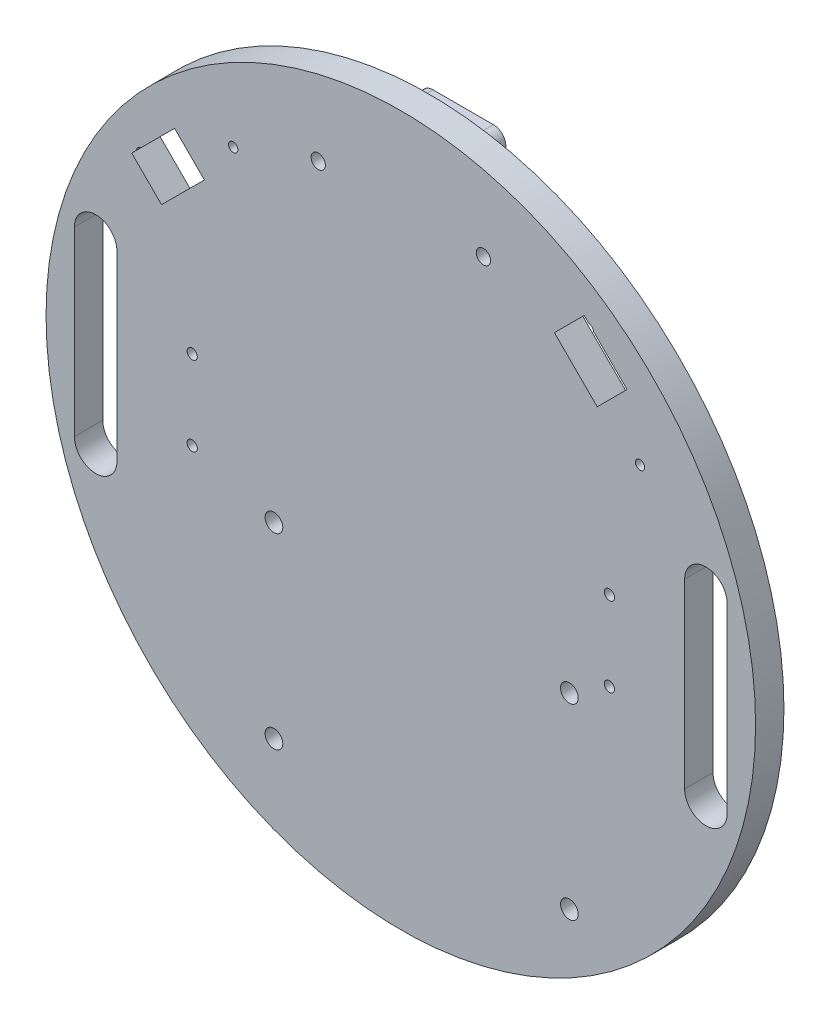
SolidWorks part; units mm, degrees
ref_plane "Front Plane" through (0, 0, 0) normal (0, 0, 1) x (1, 0, 0)
ref_plane "Top Plane" through (0, 0, 0) normal (0, 1, 0) x (1, 0, 0)
ref_plane "Right Plane" through (0, 0, 0) normal (1, 0, 0) x (0, 0, -1)
sketch "Master" plane through (0, 0, 0) normal (0, 0, 1) x (1, 0, 0)
  line L0 (-46.6725, -8.89) -> (-46.6725, 8.89) construction
  line L1 (-53.5313, 34.3674) -> (-34.3674, 53.5313) construction
  line L2 (-79.375, -79.375) -> (79.375, -79.375) construction
  line L3 (-79.375, -79.375) -> (-79.375, 79.375) construction
  line L4 (-79.375, 79.375) -> (79.375, 79.375) construction
  line L5 (79.375, -79.375) -> (79.375, 79.375) construction
  line L6 (-79.375, -79.375) -> (79.375, 79.375) construction
  line L7 (-68.2625, 20.32) -> (-68.2625, -20.32) construction
  line L8 (-63.5, 20.32) -> (-63.5, -20.32)
  line L9 (-73.025, 20.32) -> (-73.025, -20.32)
  line L10 (0, 79.375) -> (0, -79.375) construction
  line L11 (68.2625, 20.32) -> (68.2625, -20.32) construction
  line L14 (-18.4785, 60.3123) -> (18.4785, 60.3123) construction
  line L15 (-28.39, -14.615) -> (37.71, -14.615) construction
  line L16 (-28.39, -14.615) -> (-28.39, -56.515) construction
  line L17 (-28.39, -56.515) -> (37.71, -56.515) construction
  line L18 (37.71, -14.615) -> (37.71, -56.515) construction
  line L19 (-14.732, 66.8782) -> (14.732, 66.8782) construction
  line L20 (-14.732, 66.8782) -> (-14.732, 64.0588) construction
  line L21 (-43, -8.255) -> (43, -8.255) construction
  line L22 (-43, -8.255) -> (-43, -62.865) construction
  line L23 (-43, -62.865) -> (43, -62.865) construction
  line L24 (43, -8.255) -> (43, -62.865) construction
  line L25 (-43, -8.255) -> (43, -62.865) construction
  line L26 (-43, -62.865) -> (43, -8.255) construction
  line L27 (-14.732, 53.7718) -> (14.732, 53.7718) construction
  line L28 (14.732, 66.8782) -> (14.732, 64.0588) construction
  line L29 (-14.732, 66.8782) -> (14.732, 53.7718) construction
  line L30 (-14.732, 53.7718) -> (14.732, 66.8782) construction
  line L31 (-18.4785, 64.0588) -> (-14.732, 64.0588) construction
  line L32 (-18.4785, 56.5658) -> (-14.732, 56.5658) construction
  line L33 (14.732, 64.0588) -> (18.4785, 64.0588) construction
  line L34 (14.732, 56.5658) -> (18.4785, 56.5658) construction
  line L35 (-14.732, 56.5658) -> (-14.732, 53.7718) construction
  line L36 (14.732, 56.5658) -> (14.732, 53.7718) construction
  line L37 (-79.375, 79.375) -> (79.375, -79.375) construction
  line L38 (-53.5313, 34.3674) -> (-61.2184, 42.0545) construction
  line L39 (-61.2184, 42.0545) -> (-42.0545, 61.2184) construction
  line L40 (-34.3674, 53.5313) -> (-42.0545, 61.2184) construction
  line L41 (-53.5313, 34.3674) -> (-42.0545, 61.2184) construction
  line L42 (-61.2184, 42.0545) -> (-34.3674, 53.5313) construction
  line L43 (34.3674, 53.5313) -> (53.5313, 34.3674) construction
  line L44 (34.3674, 53.5313) -> (42.0545, 61.2184) construction
  line L45 (42.0545, 61.2184) -> (61.2184, 42.0545) construction
  line L46 (53.5313, 34.3674) -> (61.2184, 42.0545) construction
  line L47 (34.3674, 53.5313) -> (61.2184, 42.0545) construction
  line L48 (42.0545, 61.2184) -> (53.5313, 34.3674) construction
  line L49 (0, 0) -> (-34.3674, 53.5313) construction
  line L50 (63.5, 20.32) -> (63.5, -20.32)
  line L51 (-66.04, -5.08) -> (-27.305, -5.08) construction
  line L52 (-66.04, -5.08) -> (-66.04, 5.08) construction
  line L53 (-66.04, 5.08) -> (-27.305, 5.08) construction
  line L54 (-27.305, -5.08) -> (-27.305, 5.08) construction
  line L55 (-66.04, -5.08) -> (-27.305, 5.08) construction
  line L56 (-66.04, 5.08) -> (-27.305, -5.08) construction
  line L57 (73.025, 20.32) -> (73.025, -20.32)
  line L58 (66.04, 5.08) -> (27.305, 5.08) construction
  line L59 (66.04, 5.08) -> (27.305, -5.08) construction
  line L60 (27.305, -5.08) -> (27.305, 5.08) construction
  line L61 (66.04, -5.08) -> (27.305, 5.08) construction
  line L62 (66.04, -5.08) -> (27.305, -5.08) construction
  line L63 (-53.5313, 34.3674) -> (-43.9494, 43.9494)
  line L64 (-53.5313, 34.3674) -> (-60.2006, 41.0367)
  line L65 (-43.9494, 43.9494) -> (-50.6187, 50.6187)
  line L66 (-60.2006, 41.0367) -> (-50.6187, 50.6187)
  line L67 (34.3674, 53.5313) -> (43.9494, 43.9494)
  line L68 (34.3674, 53.5313) -> (41.0367, 60.2006)
  line L69 (43.9494, 43.9494) -> (50.6187, 50.6187)
  line L70 (41.0367, 60.2006) -> (50.6187, 50.6187)
  line L71 (0, 0) -> (-50.6187, 50.6187) construction
  circle A0 centre (0, 0) radius 79.375
  arc A1 (-63.5, 20.32) -> (-73.025, 20.32) centre (-68.2625, 20.32) ccw
  arc A2 (-73.025, -20.32) -> (-63.5, -20.32) centre (-68.2625, -20.32) ccw
  circle A3 centre (-46.6725, -8.89) radius 1.143
  circle A4 centre (-46.6725, 8.89) radius 1.143
  arc A7 (63.5, 20.32) -> (73.025, 20.32) centre (68.2625, 20.32) cw
  arc A8 (73.025, -20.32) -> (63.5, -20.32) centre (68.2625, -20.32) cw
  circle A9 centre (-28.39, -14.615) radius 1.9844
  circle A10 centre (37.71, -14.615) radius 1.9844
  circle A11 centre (37.71, -56.515) radius 1.9844
  circle A12 centre (-28.39, -56.515) radius 1.9844
  arc A13 (-18.4785, 64.0588) -> (-18.4785, 56.5658) centre (-18.4785, 60.3123) ccw construction
  arc A14 (18.4785, 56.5658) -> (18.4785, 64.0588) centre (18.4785, 60.3123) ccw construction
  circle A15 centre (-18.4785, 60.3123) radius 1.6002
  circle A16 centre (18.4785, 60.3123) radius 1.6002
  circle A17 centre (-58.0933, 42.0545) radius 1.0414
  circle A18 centre (-37.4926, 53.5313) radius 1.0414
  circle A19 centre (42.0545, 58.0933) radius 1.0414
  circle A20 centre (53.5313, 37.4926) radius 1.0414
  circle A21 centre (46.6725, -8.89) radius 1.143
  circle A22 centre (46.6725, 8.89) radius 1.143
  point P3 (-79.375, 0)
  point P4 (79.375, 0)
  point P6 (0, -79.375)
  point P9 (-46.6725, 0)
  point P12 (-68.2625, 0)
  point P23 (68.2625, 0)
  point P45 (0, -35.56)
  point P48 (0, 60.325)
  point P50 (0, 44.5902)
  point P63 (0, 79.375)
  point P71 (-47.7929, 47.7929)
  point P76 (-56.1266, 56.1266)
  point P77 (-46.6725, 0)
  point P79 (0, -62.865)
  point P84 (47.7929, 47.7929)
  point P89 (56.1266, 56.1266)
  dimension "D1" = 40.64
  dimension "D4" = 2.286
  dimension "D7" = 3.9688
  dimension "D8" = 86
  dimension "D17" = 3.2004
  dimension "D18" = 3.2004
  dimension "D23" = 2.0828
  dimension "D24" = 2.0828
  dimension "D38" = 158.75
  dimension "D2" = 9.525
  dimension "D3" = 21.59
  dimension "D5" = 66.1
  dimension "D6" = 41.9
  dimension "D9" = 54.61
  dimension "D10" = 14.61
  dimension "D11" = 6.35
  dimension "D12" = 29.464
  dimension "D13" = 36.957
  dimension "D14" = 7.493
  dimension "D15" = 13.1064
  dimension "D16" = 2.8194
  dimension "D19" = 17.78
  dimension "D20" = 19.05
  dimension "D21" = 10.8712
  dimension "D22" = 27.1018
  dimension "D25" = 2.2098
  dimension "D26" = 2.2098
  dimension "D27" = 2.2098
  dimension "D28" = 2.2098
  dimension "D29" = 6.35
  dimension "D32" = 6.35
  dimension "D33" = 16.51
  dimension "D34" = 45.72
  dimension "D35" = 10.16
  dimension "D30" = 2
  dimension "D36" = 2
extrude "Boss-Extrude1" add sketch "Master" along normal blind 6.35 contours A0 A21 A20 A19 A18 A17 A16 A15 A12 A11 A10 A9 A4 A3 A2 L9 A1 L8 L57 A8 L50 A7 A22
sketch "Sketch11" plane through (0, 0, 0) normal (0, 0, 1) x (1, 0, 0)
  line L0 (6.7691, 70.2691) -> (-6.7691, 70.2691) construction
  line L1 (6.7691, 67.5132) -> (-6.7691, 67.5132)
  line L2 (6.7691, 73.025) -> (-6.7691, 73.025)
  line L3 (0, 0) -> (-27.6628, 0) construction
  line L4 (0, 79.375) -> (0, -79.375) construction
  line L5 (6.7691, -70.2691) -> (-6.7691, -70.2691) construction
  line L6 (6.7691, -67.5132) -> (-6.7691, -67.5132)
  line L7 (6.7691, -73.025) -> (-6.7691, -73.025)
  arc A0 (6.7691, 67.5132) -> (6.7691, 73.025) centre (6.7691, 70.2691) ccw
  arc A1 (-6.7691, 73.025) -> (-6.7691, 67.5132) centre (-6.7691, 70.2691) ccw
  circle A2 centre (-6.7691, 70.2691) radius 1.143
  circle A3 centre (6.7691, 70.2691) radius 1.143
  arc A4 (6.7691, -67.5132) -> (6.7691, -73.025) centre (6.7691, -70.2691) cw
  arc A5 (-6.7691, -73.025) -> (-6.7691, -67.5132) centre (-6.7691, -70.2691) cw
  circle A6 centre (6.7691, -70.2691) radius 1.143
  circle A7 centre (-6.7691, -70.2691) radius 1.143
  point P2 (0, 70.2691)
  point P7 (-9.525, 70.2691)
  point P8 (9.525, 70.2691)
  point P21 (0, -70.2691)
  point P30 (9.525, -70.2691)
  point P31 (-9.525, -70.2691)
  dimension "D3" = 2.286
  dimension "D1" = 19.05
  dimension "D2" = 13.5382
  dimension "D4" = 6.35
extrude "Boss-Extrude3" add sketch "Sketch11" against normal blind 7.62
sketch "Sketch13" plane through (0, 73.025, 0) normal (0, 1, 0) x (1, 0, 0)
  line L0 (6.7691, 7.62) -> (6.7691, 0) construction
  line L1 (-6.7691, 0) -> (6.7691, 0)
  line L2 (-6.7691, 0) -> (-6.7691, 5.08)
  line L3 (-6.7691, 5.08) -> (6.7691, 5.08)
  line L4 (6.7691, 0) -> (6.7691, 5.08)
  dimension "D1" = 5.08
extrude "Cut-Extrude1" cut sketch "Sketch13" against normal through all
